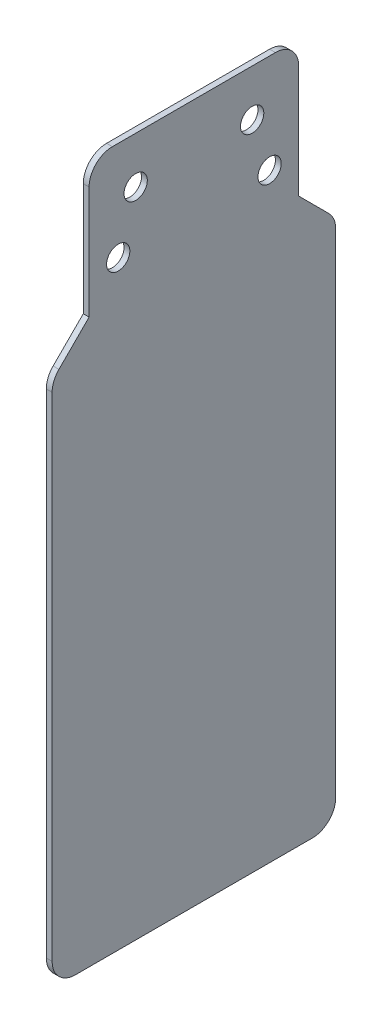
SolidWorks part; units mm, degrees
material "PVC 0.007 Plasticized"
ref_plane "Front Plane" through (0, 0, 0) normal (0, 0, 1) x (1, 0, 0)
ref_plane "Top Plane" through (0, 0, 0) normal (0, 1, 0) x (1, 0, 0)
ref_plane "Right Plane" through (0, 0, 0) normal (1, 0, 0) x (0, 0, -1)
sketch "Sketch1" plane through (0, 0, 0) normal (1, 0, 0) x (0, 0, -1)
  line L1 (-18, 0) -> (18, 0)
  line L2 (-18, 0) -> (-18, -120)
  line L3 (-18, -120) -> (18, -120)
  line L4 (18, 0) -> (18, -120)
  line L5 (-18, 0) -> (18, -120) construction
  line L6 (-18, -120) -> (18, 0) construction
  point P4 (0, -60)
  point P5 (0, 0)
  dimension "D1" = 120
  dimension "D2" = 36
extrude "Boss-Extrude1" add sketch "Sketch1" along normal blind 1 contours L2 L3 L4 L1
hole_wizard "Ø4.0 (4) Diameter Hole2" positions "Sketch2" profile "Sketch3" hole size "Ø4.0" standard "ISO" end condition through all
sketch "Sketch2" plane through (0, 0, 0) normal (-1, 0, 0) x (0, 0, 1)
  line L0 (18, 0) -> (-18, 0) construction
  line L1 (18, 0) -> (18, -120) construction
  line L2 (-18, 0) -> (-18, -120) construction
  point P0 (-10, -8)
  point P3 (10, -8)
  dimension "D1" = 8
  dimension "D2" = 8
  dimension "D3" = 8
  dimension "D4" = 8
sketch "Sketch3" plane through (0, -8, -10) normal (0, 1, 0) x (0, 0, 1)
  line L0 (0, 0) -> (0, 1)
  line L1 (0, 1) -> (2, 1)
  line L2 (2, 1) -> (2, 0)
  line L5 (2, 0) -> (0, 0)
  line L11 (0, -6.35) -> (0, 107.95) construction
  dimension "Thru Hole Dia." = 4
  dimension "Thru Hole Depth" = 1
hole_wizard "Ø4.0 (4) Diameter Hole3" positions "Sketch4" profile "Sketch5" hole size "Ø4.0" standard "ISO" end condition through all
sketch "Sketch4" plane through (0, 0, 0) normal (-1, 0, 0) x (0, 0, 1)
  line L0 (-18, 0) -> (-18, -120) construction
  line L1 (18, 0) -> (18, -120) construction
  line L2 (18, 0) -> (-18, 0) construction
  point P0 (-13, -17)
  point P3 (13, -17)
  dimension "D1" = 5
  dimension "D2" = 5
  dimension "D3" = 17
  dimension "D4" = 17
sketch "Sketch5" plane through (0, -17, -13) normal (0, 1, 0) x (0, 0, 1)
  line L0 (0, 0) -> (0, 1)
  line L1 (0, 1) -> (2, 1)
  line L2 (2, 1) -> (2, 0)
  line L5 (2, 0) -> (0, 0)
  line L11 (0, -6.35) -> (0, 107.95) construction
  dimension "Thru Hole Dia." = 4
  dimension "Thru Hole Depth" = 1
sketch "Sketch6" plane through (1, 0, 0) normal (1, 0, 0) x (0, 0, -1)
  line L0 (-18, -120) -> (18, -120) construction
  point P0 (-6, -114)
  point P1 (6, -114)
  dimension "D1" = 12
  dimension "D2" = 6
  dimension "D3" = 6
sketch "Sketch9" plane through (0, 0, 0) normal (-1, 0, 0) x (0, 0, 1)
  line L0 (18, -23.35) -> (23.1784, -28.5284)
  line L1 (18, 0) -> (18, -120) construction
  line L2 (24.35, -31.3569) -> (24.35, -116)
  line L3 (20.35, -120) -> (18, -120)
  line L4 (18, -120) -> (18, -23.35)
  line L5 (-18, -23.35) -> (-23.1784, -28.5284)
  line L6 (-18, 0) -> (-18, -120) construction
  line L7 (-24.35, -31.3569) -> (-24.35, -116)
  line L8 (-20.35, -120) -> (-18, -120)
  line L9 (-18, -120) -> (-18, -23.35)
  circle A0 centre (13, -17) radius 2 construction
  circle A2 centre (-13, -17) radius 2 construction
  arc A3 (24.35, -116) -> (20.35, -120) centre (20.35, -116) cw
  arc A4 (-24.35, -116) -> (-20.35, -120) centre (-20.35, -116) ccw
  arc A5 (23.1784, -28.5284) -> (24.35, -31.3569) centre (20.35, -31.3569) cw
  arc A6 (-23.1784, -28.5284) -> (-24.35, -31.3569) centre (-20.35, -31.3569) ccw
  dimension "D2" = 6.35
  dimension "D5" = 6.35
  dimension "D7" = 4
  dimension "D1" = 6.35
  dimension "D3" = 45
  dimension "D4" = 6.35
  dimension "D6" = 45
extrude "Boss-Extrude2" add sketch "Sketch9" against normal up to surface (1 mm away) up to face at (1, -17, -11)
fillet "Fillet1" radius 4 2 edges at (0.5, 0, 18) (0.5, 0, -18)
